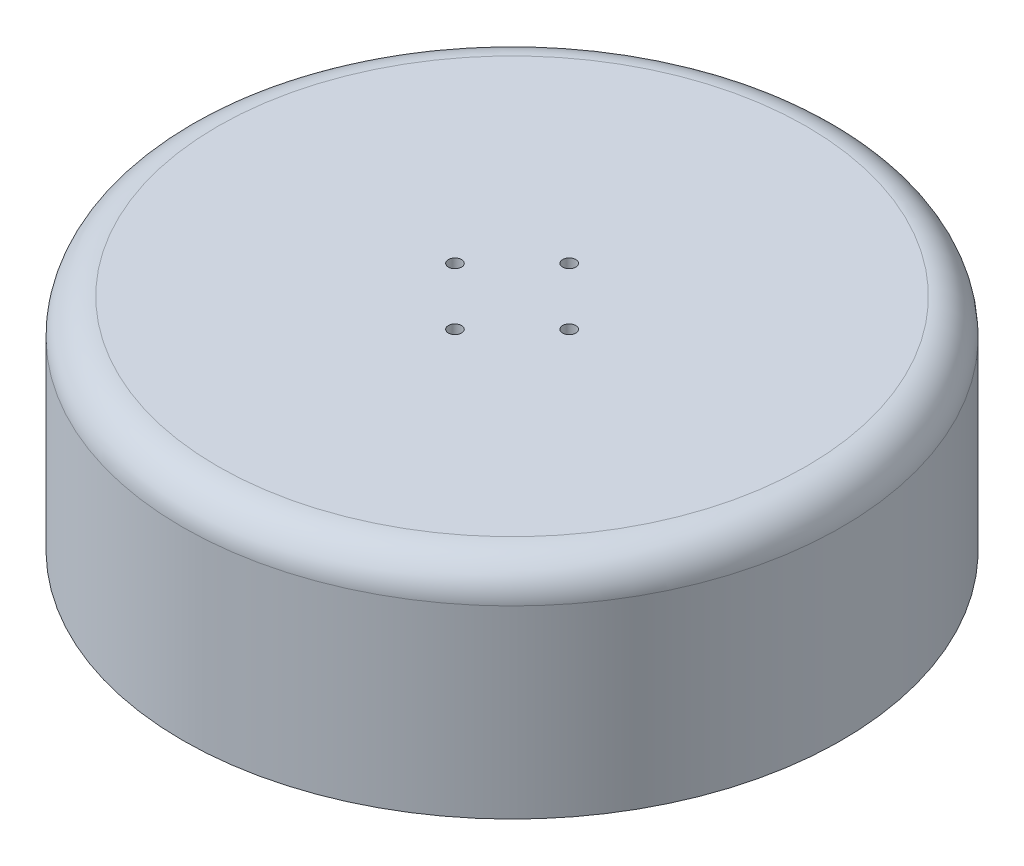
SolidWorks part; units mm, degrees
ref_plane "Front Plane" through (0, 0, 0) normal (0, 0, 1) x (1, 0, 0)
ref_plane "Top Plane" through (0, 0, 0) normal (0, 1, 0) x (1, 0, 0)
ref_plane "Right Plane" through (0, 0, 0) normal (1, 0, 0) x (0, 0, -1)
sketch "Sketch1" plane through (0, 0, 0) normal (0, 1, 0) x (1, 0, 0)
  circle A0 centre (0, 0) radius 75
  dimension "D1" = 150
extrude "Boss-Extrude1" add sketch "Sketch1" along normal blind 50
fillet "Fillet1" radius 8 1 edges at (0, 50, 75)
sketch "Sketch2" plane through (0, 50, 0) normal (0, 1, 0) x (1, 0, 0)
  circle A0 centre (0, 0) radius 13 construction
  circle A1 centre (0, 13) radius 1.5
  circle A2 centre (13, 0) radius 1.5
  circle A3 centre (0, -13) radius 1.5
  circle A4 centre (-13, 0) radius 1.5
  point P14 (0, 0)
  dimension "D1" = 26
  dimension "D2" = 3
  dimension "D3" = 4
extrude "Cut-Extrude1" cut sketch "Sketch2" against normal blind 4
